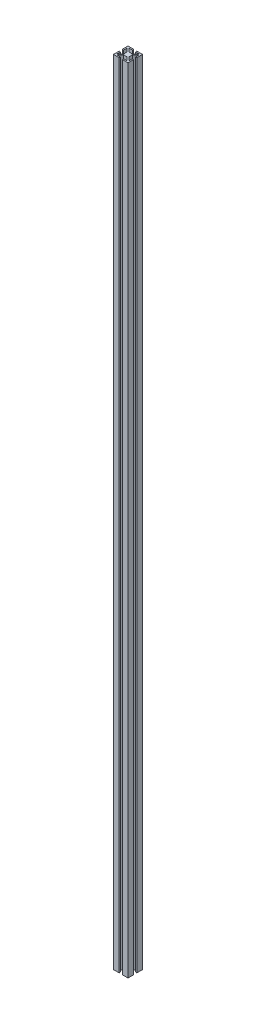
SolidWorks part; units mm, degrees
ref_plane "Front Plane" through (0, 0, 0) normal (0, 0, 1) x (1, 0, 0)
ref_plane "Top Plane" through (0, 0, 0) normal (0, 1, 0) x (1, 0, 0)
ref_plane "Right Plane" through (0, 0, 0) normal (1, 0, 0) x (0, 0, -1)
sketch "Sketch1" plane through (11.365, 0, 9.8462) normal (0, 1, 0) x (1, 0, 0)
  line L0 (-11.365, 9.8462) -> (-11.365, 32.3924) construction
  line L1 (-11.365, 9.8462) -> (-35.43, 9.8462) construction
  line L2 (-11.365, 9.8462) -> (-7.5972, 6.0784) construction
  line L3 (-24.065, 22.5462) -> (-14.2298, 22.5462)
  line L4 (-14.2298, 22.5462) -> (-14.2298, 20.3364)
  line L5 (-14.2298, 20.3364) -> (-20.2926, 20.3364)
  line L6 (-20.2926, 20.3364) -> (-14.3109, 14.3547)
  line L7 (-14.3109, 14.3547) -> (-8.4191, 14.3547)
  line L8 (-15.8735, 12.7921) -> (-15.8735, 6.9003)
  line L9 (-21.8552, 18.7738) -> (-15.8735, 12.7921)
  line L10 (-21.8552, 12.711) -> (-21.8552, 18.7738)
  line L11 (-24.065, 12.711) -> (-21.8552, 12.711)
  line L12 (-24.065, 22.5462) -> (-24.065, 12.711)
  line L13 (-14.3109, 5.3377) -> (-8.4191, 5.3377)
  line L14 (-20.2926, -0.644) -> (-14.3109, 5.3377)
  line L15 (-21.8552, 0.9186) -> (-15.8735, 6.9003)
  line L16 (-21.8552, 6.9814) -> (-21.8552, 0.9186)
  line L17 (-24.065, 6.9814) -> (-21.8552, 6.9814)
  line L18 (-24.065, -2.8538) -> (-24.065, 6.9814)
  line L19 (-14.2298, -0.644) -> (-20.2926, -0.644)
  line L20 (-14.2298, -2.8538) -> (-14.2298, -0.644)
  line L21 (-24.065, -2.8538) -> (-14.2298, -2.8538)
  line L22 (1.335, -2.8538) -> (-8.5002, -2.8538)
  line L23 (-8.5002, -2.8538) -> (-8.5002, -0.644)
  line L24 (-8.5002, -0.644) -> (-2.4374, -0.644)
  line L25 (1.335, -2.8538) -> (1.335, 6.9814)
  line L26 (1.335, 6.9814) -> (-0.8748, 6.9814)
  line L27 (-0.8748, 6.9814) -> (-0.8748, 0.9186)
  line L28 (-0.8748, 0.9186) -> (-6.8565, 6.9003)
  line L29 (-2.4374, -0.644) -> (-8.4191, 5.3377)
  line L30 (1.335, 22.5462) -> (1.335, 12.711)
  line L31 (1.335, 12.711) -> (-0.8748, 12.711)
  line L32 (-0.8748, 12.711) -> (-0.8748, 18.7738)
  line L33 (-0.8748, 18.7738) -> (-6.8565, 12.7921)
  line L34 (-6.8565, 12.7921) -> (-6.8565, 6.9003)
  line L35 (-2.4374, 20.3364) -> (-8.4191, 14.3547)
  line L36 (-8.5002, 20.3364) -> (-2.4374, 20.3364)
  line L37 (-8.5002, 22.5462) -> (-8.5002, 20.3364)
  line L38 (1.335, 22.5462) -> (-8.5002, 22.5462)
  point P20 (-15.8735, 9.8462)
  point P26 (-6.8565, 9.8462)
  point P36 (-11.365, 5.3377)
  point P42 (-11.365, 14.3547)
  dimension "D1" = 9.8352
  dimension "D2" = 12.7
  dimension "D3" = 4.5085
  dimension "D4" = 2.2098
  dimension "D5" = 1.1049
extrude "Boss-Extrude1" add sketch "Sketch1" along normal up to surface (1384.3 mm away)
other "1010<1>"
